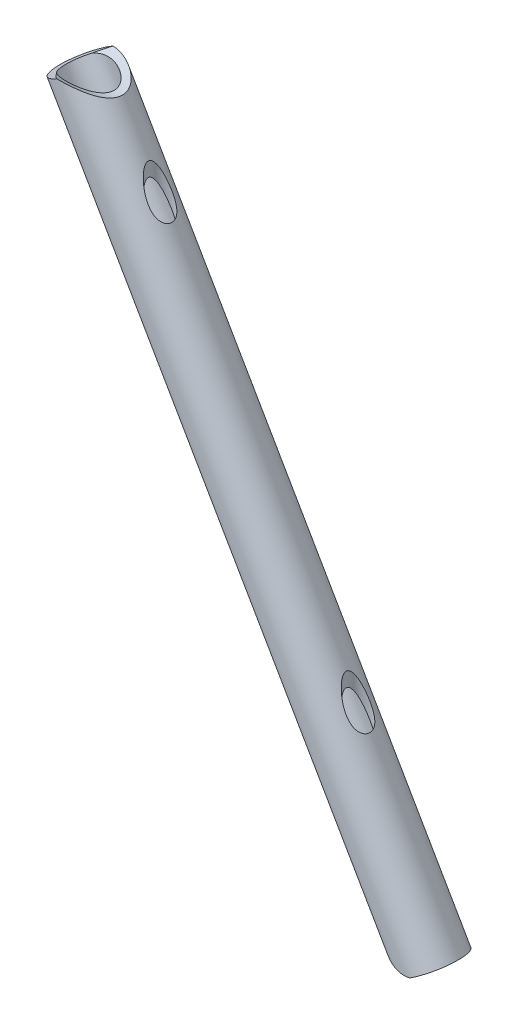
SolidWorks part; units mm, degrees
ref_plane "Front Plane" through (0, 0, 0) normal (0, 0, 1) x (1, 0, 0)
ref_plane "Top Plane" through (0, 0, 0) normal (0, 1, 0) x (1, 0, 0)
ref_plane "Right Plane" through (0, 0, 0) normal (1, 0, 0) x (0, 0, -1)
sketch "Sketch1" plane through (0, 0, 0) normal (0, 0, 1) x (1, 0, 0)
  line L0 (0, 0) -> (-117.3176, 203.2)
  line L1 (-117.3176, 203.2) -> (-117.3176, 0) construction
  line L2 (-117.3176, 0) -> (-91.9176, 0) construction
  line L3 (0, 0) -> (-25.4, 0) construction
  line L4 (-25.4, 0) -> (-91.9176, 0) construction
  dimension "D1" = 25.4
  dimension "D2" = 203.2
  dimension "D3" = 117.3176
  dimension "D4" = 234.6351
  dimension "D5" = 25.4
  dimension "D6" = 60
  dimension "D7" = 66.5176
ref_plane "Plane1" through (0, 0, 0) normal (-0.5, 0.866, 0) x (0, 0, 1)
sketch "Sketch2" plane through (0, 0, 0) normal (-0.5, 0.866, 0) x (0, 0, 1)
  circle A0 centre (0, 0) radius 7.112
  circle A1 centre (0, 0) radius 9.525
  dimension "D1" = 2.413
  dimension "D2" = 19.05
sweep "Sweep1" add profiles "Sketch2" path "Sketch1"
sketch "Sketch4" plane through (0, 0, 0) normal (0, 1, 0) x (1, 0, 0)
  line L0 (-25.4, 0) -> (-91.92, 0) construction
  line L1 (-25.4, 0) -> (0, 0) construction
  circle A0 centre (-25.4, 0) radius 4
  circle A1 centre (-91.92, 0) radius 4
  dimension "D1" = 25.4
  dimension "D2" = 8
  dimension "D3" = 66.52
  dimension "D4" = 8
extrude "Cut-Extrude2" cut sketch "Sketch4" against normal blind 70 and the other way blind 542
sketch "Sketch5" plane through (0, 0, 0) normal (1, 0, 0) x (0, 0, -1)
  line L0 (0, 0) -> (0, 207.9625) construction
  circle A1 centre (0, -12) radius 15.875
  circle A2 centre (0, 215.9625) radius 15.875
  ellipse E0 centre (0, 203.2) end of major axis (9.525, 203.2) minor radius 4.7625 construction
  point P9 (0, -12.1752)
  point P14 (0, 0)
  point P15 (0, 511.9084)
  dimension "D1" = 31.75
  dimension "D2" = 12
  dimension "D3" = 8
extrude "Cut-Extrude3" cut sketch "Sketch5" against normal blind 311 and the other way blind 105
